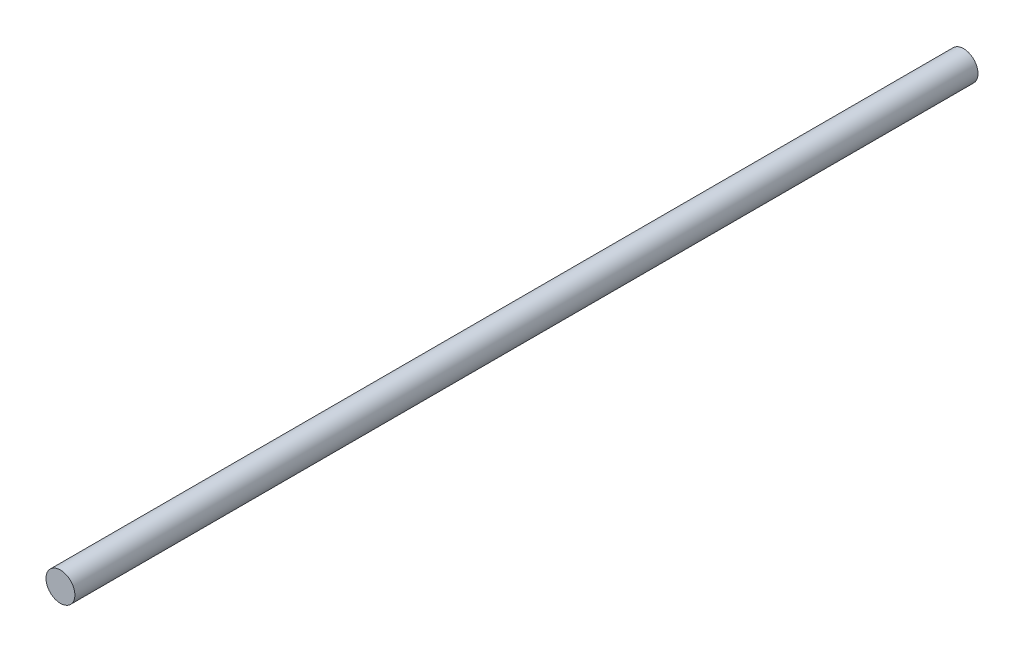
SolidWorks part; units mm, degrees
material "1.4000 (X6Cr13)"
ref_plane "Plan de face" through (0, 0, 0) normal (0, 0, 1) x (1, 0, 0)
ref_plane "Plan de dessus" through (0, 0, 0) normal (0, 1, 0) x (1, 0, 0)
ref_plane "Plan de droite" through (0, 0, 0) normal (1, 0, 0) x (0, 0, -1)
sketch "Esquisse1" plane through (0, 0, 0) normal (0, 0, 1) x (1, 0, 0)
  circle A0 centre (0, 0) radius 4
extrude "Boss.-Extru.1" add sketch "Esquisse1" along normal blind 250
ref_plane "SectionMiBarre" through (0, 0, 125) normal (0, 0, 1) x (1, 0, 0)
